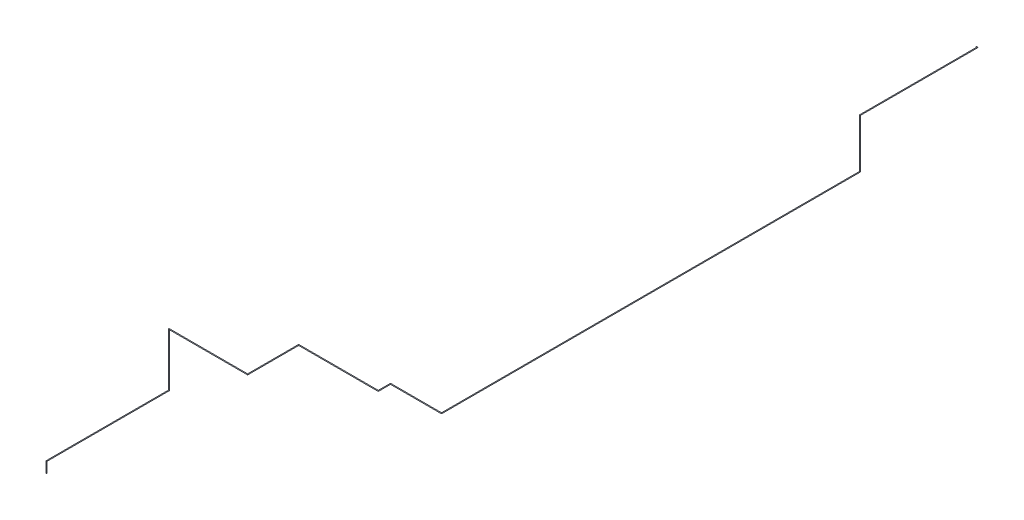
SolidWorks part; units mm, degrees
ref_plane "Alzado" through (0, 0, 0) normal (0, 0, 1) x (1, 0, 0)
ref_plane "Planta" through (0, 0, 0) normal (0, 1, 0) x (1, 0, 0)
ref_plane "Vista lateral" through (0, 0, 0) normal (1, 0, 0) x (0, 0, -1)
sketch "Croquis2" plane through (0, 0, 0) normal (0, 1, 0) x (1, 0, 0)
  circle A0 centre (0, 0) radius 12.7
  dimension "D1" = 25.4
extrude "Saliente-Extruir1" add sketch "Croquis2" along normal blind 20
sketch3d "Croquis3D1"
  line L0 (0, 20, 0) -> (0, 520, 0)
  line L1 (0, 20, 0) -> (0, 0, 0) construction
  line L2 (0, 520, 0) -> (0, 520, -6005)
  line L3 (0, 520, -6005) -> (0, 3120, -6005)
  line L4 (0, 3120, -6005) -> (3850, 3120, -6005)
  line L5 (3850, 3120, -6005) -> (3850, 3120, -8505)
  line L6 (3850, 3120, -8505) -> (7750, 3120, -8505)
  line L7 (7750, 3120, -8505) -> (7750, 3120, -9105)
  line L8 (7750, 3120, -9105) -> (10250, 3120, -9105)
  line L9 (10250, 3120, -9105) -> (10250, 3120, -29605)
  line L10 (10250, 3120, -29605) -> (10250, 5520, -29605)
  line L11 (10250, 5520, -29605) -> (10250, 5520, -35355)
  line L12 (10250, 5520, -35355) -> (10210, 5520, -35355)
  dimension "D1" = 500
  dimension "D2" = 6005
  dimension "D3" = 2600
  dimension "D4" = 3850
  dimension "D5" = 2500
  dimension "D6" = 3900
  dimension "D7" = 600
  dimension "D8" = 2500
  dimension "D9" = 20500
  dimension "D10" = 2400
  dimension "D11" = 5750
  dimension "D12" = 40
sketch "Croquis3" plane through (0, 20, 0) normal (0, 1, 0) x (1, 0, 0)
  circle A0 centre (0, 0) radius 17.5
  dimension "D1" = 35
sweep "Barrer1" add profiles "Croquis3" path "Croquis3D1"
sketch "Croquis4" plane through (0, 0, 0) normal (0, -1, 0) x (1, 0, 0)
  line L1 (-0.2558, 12.4823) -> (0.2558, 12.4823)
  line L2 (-0.2558, 12.4823) -> (-0.2558, 12.9177)
  line L3 (-0.2558, 12.9177) -> (0.2558, 12.9177)
  line L4 (0.2558, 12.4823) -> (0.2558, 12.9177)
  line L5 (-0.2558, 12.4823) -> (0.2558, 12.9177) construction
  line L6 (-0.2558, 12.9177) -> (0.2558, 12.4823) construction
  circle A0 centre (0, 0) radius 12.7 construction
  circle A1 centre (0, 0) radius 12.7 construction
  point P0 (0, 12.7)
extrude "Saliente-Extruir2" add sketch "Croquis4" against normal blind 5
